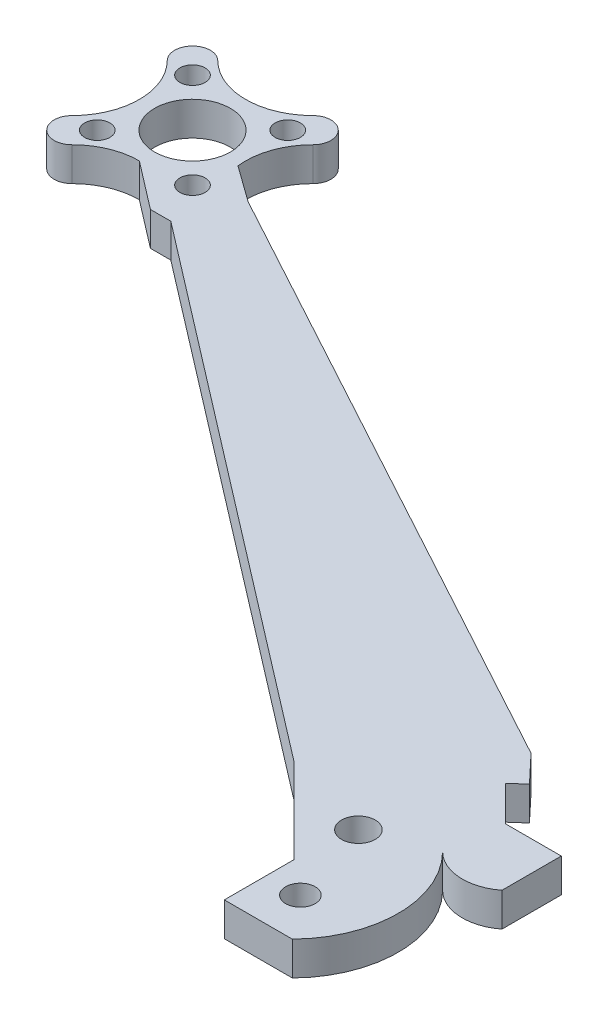
SolidWorks part; units mm, degrees
material "ABS"
ref_plane "Front Plane" through (0, 0, 0) normal (0, 0, 1) x (1, 0, 0)
ref_plane "Top Plane" through (0, 0, 0) normal (0, 1, 0) x (1, 0, 0)
ref_plane "Right Plane" through (0, 0, 0) normal (1, 0, 0) x (0, 0, -1)
sketch "Sketch1" plane through (0, 0, 0) normal (0, 1, 0) x (1, 0, 0)
  line L1 (8.155, -8.155) -> (-8.155, -8.155)
  line L2 (8.155, -8.155) -> (8.155, 8.155)
  line L3 (8.155, 8.155) -> (-8.155, 8.155)
  line L4 (-8.155, -8.155) -> (-8.155, 8.155)
  line L5 (8.155, -8.155) -> (-8.155, 8.155) construction
  line L6 (8.155, 8.155) -> (-8.155, -8.155) construction
  circle A0 centre (0, 0) radius 4.5
  dimension "D1" = 9
  dimension "D2" = 16.31
  dimension "D3" = 16.31
extrude "Boss-Extrude1" add sketch "Sketch1" along normal blind 4
sketch "Sketch3" plane through (0, 4, 0) normal (0, 1, 0) x (1, 0, 0)
  line L0 (0, 0) -> (0, 8.155) construction
  line L1 (8.155, 8.155) -> (-8.155, 8.155) construction
  line L2 (0, 0) -> (-8.155, 0) construction
  line L3 (-8.155, 8.155) -> (-8.155, -8.155) construction
  line L4 (0, 0) -> (0, -8.155) construction
  line L5 (-8.155, -8.155) -> (8.155, -8.155) construction
  line L6 (0, 0) -> (8.155, 0) construction
  line L7 (8.155, -8.155) -> (8.155, 8.155) construction
  line L8 (0, 0) -> (5.6569, 5.6569) construction
  line L9 (0, 0) -> (5.6569, -5.6569) construction
  line L10 (0, 0) -> (-5.6569, -5.6569) construction
  line L11 (0, 0) -> (-5.6569, 5.6569) construction
  circle A0 centre (5.6569, 5.6569) radius 1.5
  circle A1 centre (5.6569, -5.6569) radius 1.5
  circle A2 centre (-5.6569, -5.6569) radius 1.5
  circle A3 centre (-5.6569, 5.6569) radius 1.5
  point P22 (0, 0)
  point P29 (0, 0)
  dimension "D2" = 3
  dimension "D1" = 4
  dimension "D3" = 4
extrude "Cut-Extrude1" cut sketch "Sketch3" against normal blind 4
sketch "Sketch4" plane through (0, 4, 0) normal (0, 1, 0) x (1, 0, 0)
  line L0 (8.155, -8.155) -> (0, -8.155)
  line L1 (-8.155, -8.155) -> (8.155, -8.155) construction
  line L2 (8.155, -8.155) -> (8.155, 0)
  line L3 (8.155, -8.155) -> (8.155, 8.155) construction
  line L4 (0, -8.155) -> (0, -10.655)
  line L5 (8.155, 0) -> (10.655, 0)
  line L6 (0, -10.655) -> (10.655, -10.655)
  line L7 (10.655, -10.655) -> (10.655, 0)
extrude "Boss-Extrude2" add sketch "Sketch4" against normal blind 4
sketch "Sketch9" plane through (0, 4, 0) normal (0, 1, 0) x (1, 0, 0)
  line L0 (71.0614, -58.9826) -> (7.5931, -10.2817)
  line L1 (84.1935, -43.9826) -> (10.6138, -4.0321)
  line L2 (71.0614, -58.9826) -> (81.0614, -68.9826)
  line L3 (7.5931, -10.2817) -> (10.6138, -4.0321)
  line L4 (81.0614, -68.9826) -> (81.0614, -73.9826)
  line L5 (81.0614, -73.9826) -> (96.0614, -73.9826)
  line L6 (96.0614, -73.9826) -> (96.0614, -50.291)
  line L7 (96.0614, -50.291) -> (90.502, -50.291)
  line L8 (90.502, -50.291) -> (84.1935, -43.9826)
extrude "Boss-Extrude6" add sketch "Sketch9" against normal blind 4
sketch "Sketch12" plane through (0, 4, 0) normal (0, 1, 0) x (1, 0, 0)
  line L0 (87.2786, -47.2583) -> (85.7805, -48.5833)
  line L1 (85.7805, -48.5833) -> (89.9609, -52.761)
  line L2 (89.9609, -52.761) -> (90.502, -52.761)
  line L3 (90.502, -52.761) -> (96.0614, -52.761)
  line L4 (96.0614, -52.761) -> (96.0614, -50.291)
  line L5 (87.3477, -47.1368) -> (90.502, -50.291)
  line L6 (90.502, -50.291) -> (96.0614, -50.291)
  line L7 (90.502, -50.291) -> (96.0614, -50.291)
  line L8 (87.2786, -47.2583) -> (87.3477, -47.1368)
extrude "Cut-Extrude3" cut sketch "Sketch12" against normal blind 4 contours L8 L5 L6 L4 L3 L2 L1 L0
sketch "Sketch13" plane through (0, 4, 0) normal (0, 1, 0) x (1, 0, 0)
  line L0 (81.0614, -73.9826) -> (81.0614, -77.2826)
  line L1 (96.0614, -52.761) -> (96.5614, -52.761)
  line L2 (81.0614, -73.9826) -> (96.0614, -73.9826)
  line L3 (96.0614, -73.9826) -> (96.0614, -52.761)
  line L4 (96.5614, -52.761) -> (96.5614, -77.2826)
  line L5 (81.0614, -77.2826) -> (96.5614, -77.2826)
  dimension "D1" = 3.3
  dimension "D2" = 0.5
extrude "Boss-Extrude7" add sketch "Sketch13" against normal blind 4
sketch "Sketch16" plane through (0, 4, 0) normal (0, 1, 0) x (1, 0, 0)
  line L0 (0, -10.655) -> (-10, -10.655)
  line L1 (-10, -10.655) -> (-10, 10.345)
  line L2 (10.655, 0) -> (10.655, 10.345)
  line L3 (10.655, 10.345) -> (-10, 10.345)
  line L4 (0, -10.655) -> (0, -8.155)
  line L5 (0, -8.155) -> (-8.155, -8.155)
  line L6 (-8.155, -8.155) -> (-8.155, 8.155)
  line L7 (-8.155, 8.155) -> (8.155, 8.155)
  line L8 (8.155, 8.155) -> (8.155, 0)
  line L9 (8.155, 0) -> (10.655, 0)
  dimension "D1" = 10
  dimension "D2" = 21
extrude "Boss-Extrude9" add sketch "Sketch16" against normal blind 4
sketch "Sketch17" plane through (0, 4, 0) normal (0, 1, 0) x (1, 0, 0)
  line L0 (-5.6569, 5.6569) -> (-5.6569, 8.6569) construction
  line L1 (-5.6569, 5.6569) -> (-8.6569, 5.6569) construction
  line L2 (5.6569, 5.6569) -> (5.6569, 8.6569) construction
  line L3 (5.6569, 5.6569) -> (8.6569, 5.6569) construction
  line L4 (-5.6569, -5.6569) -> (-8.6569, -5.6569) construction
  line L5 (-5.6569, -5.6569) -> (-5.6569, -8.6569) construction
  line L6 (5.6569, -5.6569) -> (8.6569, -5.6569) construction
  line L7 (5.6569, -5.6569) -> (5.6569, -8.6569) construction
  line L8 (5.6569, -8.6569) -> (5.6569, -10.655)
  line L9 (-10, -10.655) -> (8.0797, -10.655) construction
  line L10 (8.6569, -5.6569) -> (10.655, -4.0544)
  line L11 (5.6569, -10.655) -> (8.0797, -10.655)
  line L12 (8.0797, -10.655) -> (71.0614, -58.9826)
  line L13 (71.0614, -58.9826) -> (81.0614, -68.9826)
  line L14 (81.0614, -68.9826) -> (81.0614, -77.2826)
  line L15 (81.0614, -77.2826) -> (96.5614, -77.2826)
  line L16 (96.5614, -77.2826) -> (96.5614, -52.761)
  line L17 (96.5614, -52.761) -> (89.9609, -52.761)
  line L18 (89.9609, -52.761) -> (85.7805, -48.5833)
  line L19 (85.7805, -48.5833) -> (87.2786, -47.2583)
  line L20 (87.2786, -47.2583) -> (84.1935, -43.9826)
  line L21 (84.1935, -43.9826) -> (10.655, -4.0544)
  arc A0 (-5.6569, -8.6569) -> (5.6569, -8.6569) centre (0, -14.3137) cw
  arc A1 (8.6569, 5.6569) -> (8.6569, -5.6569) centre (14.3137, 0) ccw
  arc A2 (5.6569, 8.6569) -> (-5.6569, 8.6569) centre (0, 14.3137) cw
  arc A3 (-8.6569, 5.6569) -> (-8.6569, -5.6569) centre (-14.3137, 0) cw
  arc A4 (-8.6569, 5.6569) -> (-5.6569, 8.6569) centre (-7.1569, 7.1569) cw
  arc A5 (5.6569, 8.6569) -> (8.6569, 5.6569) centre (7.1569, 7.1569) cw
  arc A6 (-8.6569, -5.6569) -> (-5.6569, -8.6569) centre (-7.1569, -7.1569) ccw
  dimension "D1" = 3
  dimension "D2" = 3
  dimension "D3" = 3
  dimension "D4" = 3
extrude "Cut-Extrude4" cut sketch "Sketch17" against normal blind 4 flip side to cut
sketch "Sketch18" plane through (0, 4, 0) normal (0, 1, 0) x (1, 0, 0)
  line L0 (5.6569, -10.655) -> (0, -6.3137)
  line L1 (0, -6.3137) -> (6.3728, -0.9706)
  line L2 (6.3728, -0.9706) -> (10.655, -4.0544)
  line L3 (10.655, -4.0544) -> (8.6569, -5.6569)
  line L4 (8.6569, -5.6569) -> (5.6569, -10.655)
  arc A0 (5.6569, -8.6569) -> (-5.6569, -8.6569) centre (0, -14.3137) ccw construction
  arc A1 (8.6569, 5.6569) -> (8.6569, -5.6569) centre (14.3137, 0) ccw construction
  circle A2 centre (5.6569, -5.6569) radius 1.5
extrude "Boss-Extrude10" add sketch "Sketch18" against normal blind 4
sketch "Sketch19" plane through (0, 4, 0) normal (0, 1, 0) x (1, 0, 0)
  line L0 (96.5614, -52.761) -> (97.0614, -52.761)
  line L1 (96.5614, -77.2826) -> (99.0224, -77.6438)
  line L2 (96.5614, -77.2826) -> (96.5614, -52.761)
  line L3 (97.0614, -52.761) -> (97.0614, -77.356)
  line L4 (97.0614, -77.356) -> (97.0614, -59.356)
  line L5 (97.0614, -77.356) -> (89.0614, -77.356)
  arc A0 (89.0614, -59.356) -> (89.0614, -77.356) centre (80.0614, -68.356) cw
  arc A1 (89.0614, -59.356) -> (97.0614, -59.356) centre (93.0614, -55.356) ccw
  dimension "D1" = 0.5
  dimension "D2" = 98.35
extrude "Cut-Extrude5" cut sketch "Sketch19" against normal blind 4 contours L4 A1 A0 L5
sketch "Sketch20" plane through (0, 0, 0) normal (0, -1, 0) x (1, 0, 0)
  line L0 (89.9609, 52.761) -> (81.8078, 62.1038) construction
  line L1 (89.9609, 52.761) -> (94.239, 52.761) construction
  line L2 (89.9609, 52.761) -> (96.5614, 52.761) construction
  circle A0 centre (81.8078, 62.1038) radius 2
  dimension "D3" = 4
  dimension "D1" = 12.4
  dimension "D2" = 131.11
extrude "Cut-Extrude6" cut sketch "Sketch20" against normal blind 10
sketch "Sketch22" plane through (0, 0, 0) normal (0, -1, 0) x (1, 0, 0)
  line L0 (85.0978, 77.2826) -> (85.0978, 72.2826)
  line L1 (81.0614, 77.2826) -> (89.1342, 77.2826) construction
  circle A0 centre (85.0978, 72.2826) radius 1.75
  dimension "D2" = 3.5
  dimension "D1" = 5
extrude "Cut-Extrude8" cut sketch "Sketch22" against normal through all contours A0
